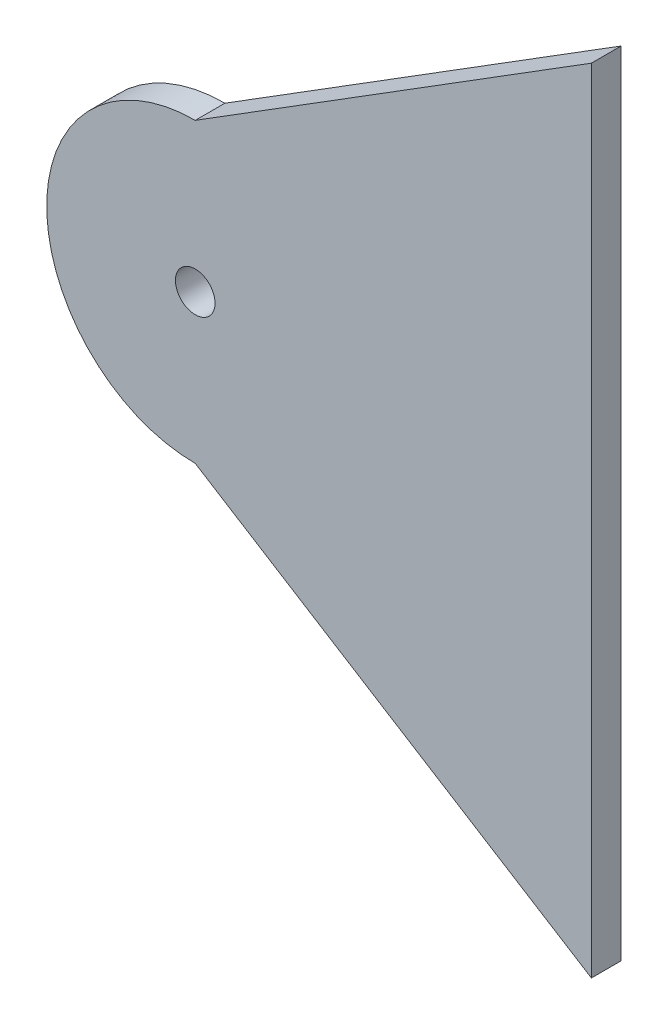
SolidWorks part; units mm, degrees
ref_plane "前视基准面" through (0, 0, 0) normal (0, 0, 1) x (1, 0, 0)
ref_plane "上视基准面" through (0, 0, 0) normal (0, 1, 0) x (1, 0, 0)
ref_plane "右视基准面" through (0, 0, 0) normal (1, 0, 0) x (0, 0, -1)
sketch "草图1" plane through (0, 0, 0) normal (0, 0, 1) x (1, 0, 0)
  line L261 (254.0026, 13.7079) -> (294.0026, 13.7079) construction
  line L264 (254.0026, 28.7079) -> (294.0026, 53.7079)
  line L269 (294.0026, 13.7079) -> (294.0026, 53.7079)
  line L271 (294.0026, 13.7079) -> (294.0026, -26.2921)
  line L274 (294.0026, -26.2921) -> (254.0026, -1.2921)
  circle A38 centre (254.0026, 13.7079) radius 2
  circle A43 centre (254.0026, 13.7079) radius 15 construction
  arc A44 (254.0026, -1.2921) -> (254.0026, 28.7079) centre (254.0026, 13.7079) cw
extrude "凸台-拉伸1" add sketch "草图1" along normal blind 3
